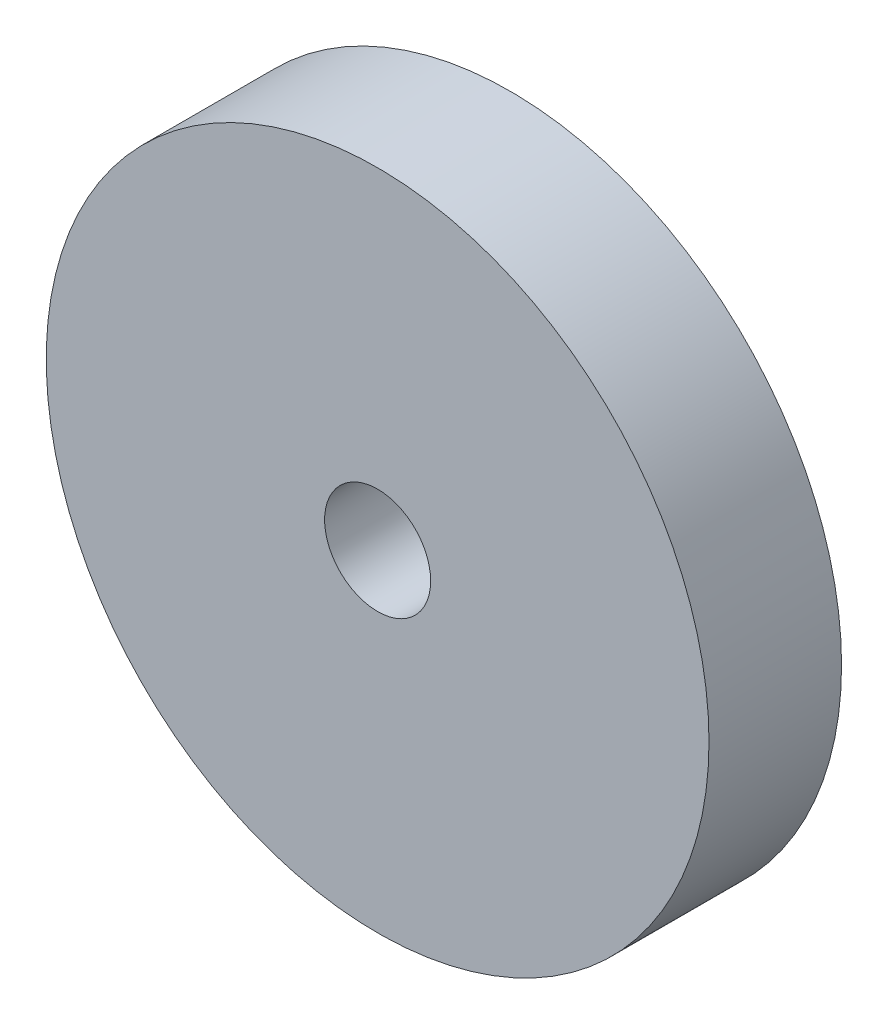
SolidWorks part; units mm, degrees
ref_plane "Alzado" through (0, 0, 0) normal (0, 0, 1) x (1, 0, 0)
ref_plane "Planta" through (0, 0, 0) normal (0, 1, 0) x (1, 0, 0)
ref_plane "Vista lateral" through (0, 0, 0) normal (1, 0, 0) x (0, 0, -1)
sketch "Croquis1" plane through (0, 0, 0) normal (0, 0, 1) x (1, 0, 0)
  circle A0 centre (0, 0) radius 25
  circle A1 centre (0, 0) radius 4
  dimension "D1" = 50
  dimension "D2" = 8
extrude "Saliente-Extruir1" add sketch "Croquis1" along normal mid plane 10
